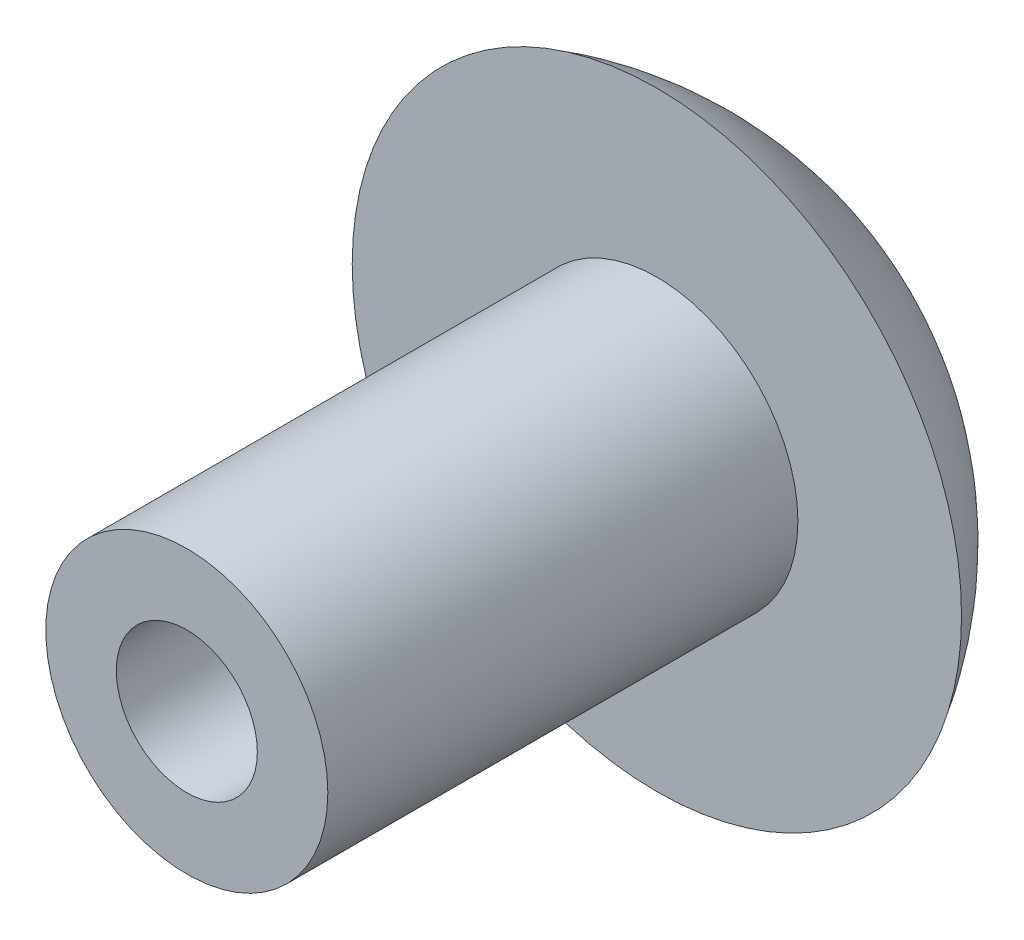
SolidWorks part; units mm, degrees
ref_plane "Front Plane" through (0, 0, 0) normal (0, 0, 1) x (1, 0, 0)
ref_plane "Top Plane" through (0, 0, 0) normal (0, 1, 0) x (1, 0, 0)
ref_plane "Right Plane" through (0, 0, 0) normal (1, 0, 0) x (0, 0, -1)
sketch "Sketch1" plane through (0, 0, 0) normal (0, 1, 0) x (1, 0, 0)
  line L0 (-65.404, 0) -> (58.8036, 0) construction
  line L1 (-7.5, 0) -> (7.5, 0)
  circle A0 centre (0, 0) radius 7.5 construction
  arc A1 (-7.5, 0) -> (7.5, 0) centre (0, 0) cw
  dimension "D1" = 15
revolve "Revolve1" add sketch "Sketch1" angle 360 about L0
sketch "Sketch2" plane through (0, 0, 0) normal (0, 1, 0) x (1, 0, 0)
  line L1 (-9.0439, 3.774) -> (9.0439, 3.774)
  line L2 (-9.0439, 3.774) -> (-9.0439, -7.5941)
  line L3 (-9.0439, -7.5941) -> (9.0439, -7.5941)
  line L4 (9.0439, 3.774) -> (9.0439, -7.5941)
  line L5 (-9.0439, 3.774) -> (9.0439, -7.5941) construction
  line L6 (-9.0439, -7.5941) -> (9.0439, 3.774) construction
  point P0 (0, -1.91)
extrude "Cut-Extrude1" cut sketch "Sketch2" against normal through all both and the other way through all contours L2 L3 L4 L1
sketch "Sketch3" plane through (0, 0, -3.774) normal (0, 0, 1) x (1, 0, 0)
  circle A0 centre (0, 0) radius 3
  dimension "D1" = 6
extrude "Boss-Extrude1" add sketch "Sketch3" along normal blind 10
sketch "Sketch4" plane through (0, 0, 6.226) normal (0, 0, 1) x (1, 0, 0)
  circle A0 centre (0, 0) radius 1.5
  dimension "D1" = 3
extrude "Cut-Extrude2" cut sketch "Sketch4" against normal blind 10 contours A0
